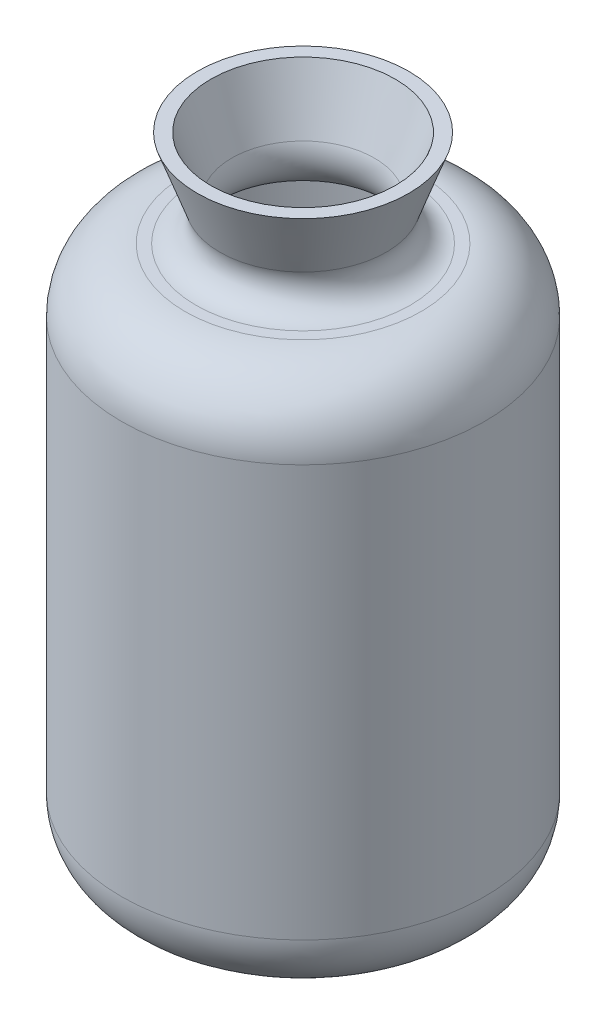
SolidWorks part; units mm, degrees
ref_plane "Front Plane" through (0, 0, 0) normal (0, 0, 1) x (1, 0, 0)
ref_plane "Top Plane" through (0, 0, 0) normal (0, 1, 0) x (1, 0, 0)
ref_plane "Right Plane" through (0, 0, 0) normal (1, 0, 0) x (0, 0, -1)
sketch "Sketch1" plane through (0, 0, 0) normal (0, 0, 1) x (1, 0, 0)
  line L0 (0, 68.3137) -> (0, -58.6863) construction
  line L1 (0, 68.3137) -> (-21.1602, 68.3137)
  line L2 (-21.1602, 68.3137) -> (-16.6581, 55.8668)
  line L3 (-21.4352, 49.0589) -> (-23.6183, 49.0589)
  line L4 (-36.3183, 36.3589) -> (-36.3183, -45.9863)
  line L5 (-23.6183, -58.6863) -> (0, -58.6863)
  line L6 (0, 68.3137) -> (0, -58.6863)
  arc A0 (-21.4352, 49.0589) -> (-16.6581, 55.8668) centre (-21.4352, 54.1389) ccw
  arc A1 (-36.3183, -45.9863) -> (-23.6183, -58.6863) centre (-23.6183, -45.9863) ccw
  arc A2 (-23.6183, 49.0589) -> (-36.3183, 36.3589) centre (-23.6183, 36.3589) ccw
  dimension "D2" = 5.08
  dimension "D3" = 12.7
  dimension "D1" = 127
revolve "Revolve1" add sketch "Sketch1" angle 360 about L0
shell "Shell1" thickness 2.54
